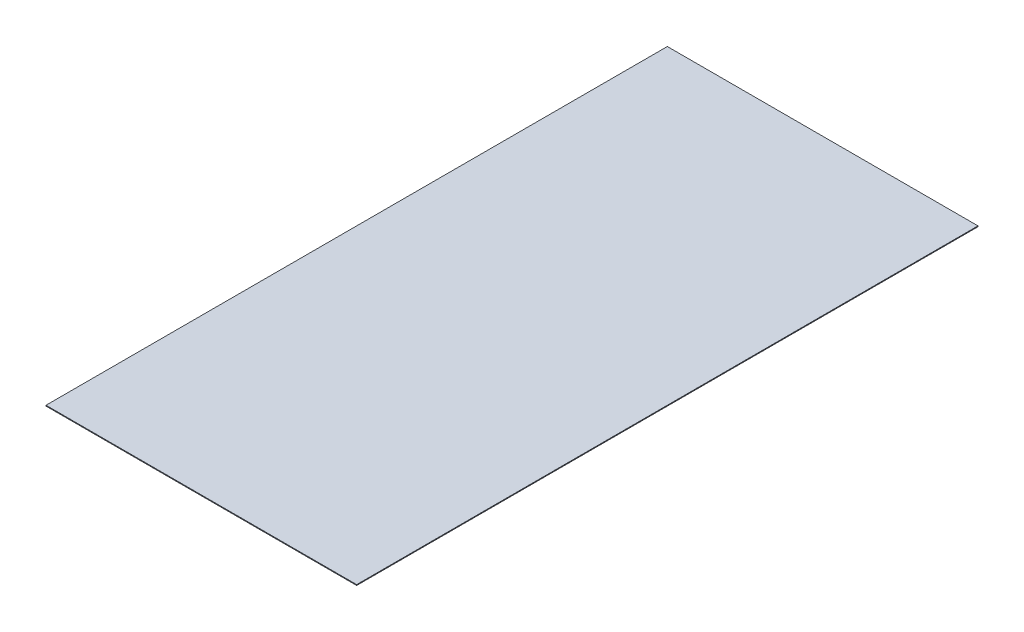
SolidWorks part; units mm, degrees
ref_plane "Front Plane" through (0, 0, 0) normal (0, 0, 1) x (1, 0, 0)
ref_plane "Top Plane" through (0, 0, 0) normal (0, 1, 0) x (1, 0, 0)
ref_plane "Right Plane" through (0, 0, 0) normal (1, 0, 0) x (0, 0, -1)
sketch "Sketch1" plane through (0, 0, 0) normal (0, 1, 0) x (1, 0, 0)
  line L1 (0, 0) -> (400, 0)
  line L2 (0, 0) -> (0, 800)
  line L3 (0, 800) -> (400, 800)
  line L4 (400, 0) -> (400, 800)
  dimension "D1" = 800
  dimension "D2" = 400
extrude "Boss-Extrude1" add sketch "Sketch1" along normal blind 1
